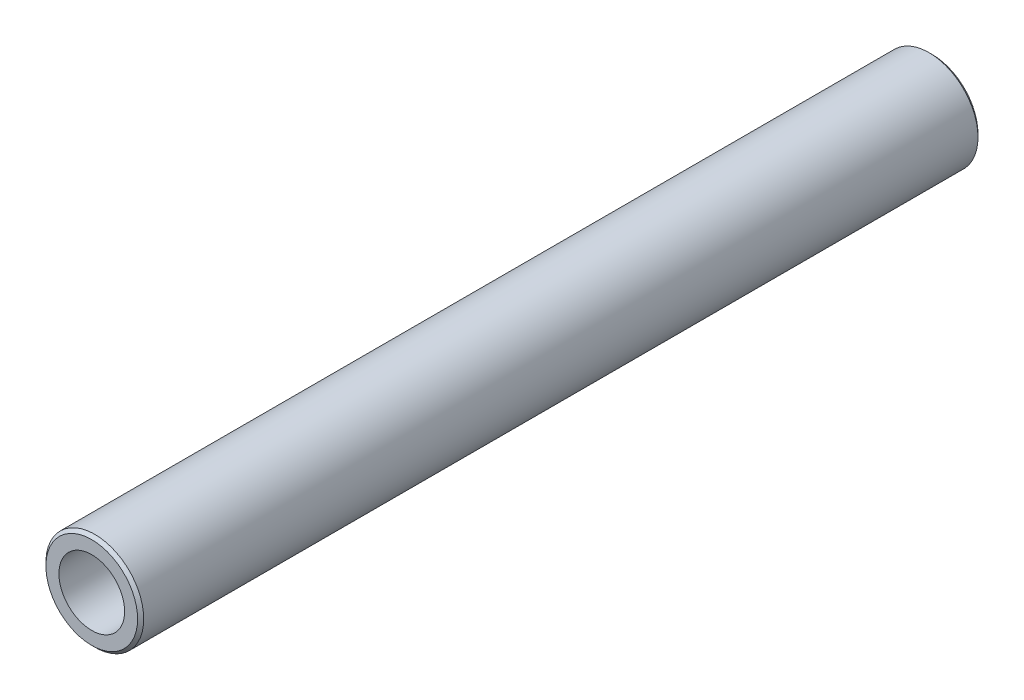
SolidWorks part; units mm, degrees
ref_plane "Front Plane" through (0, 0, 0) normal (0, 0, 1) x (1, 0, 0)
ref_plane "Top Plane" through (0, 0, 0) normal (0, 1, 0) x (1, 0, 0)
ref_plane "Right Plane" through (0, 0, 0) normal (1, 0, 0) x (0, 0, -1)
sketch "Sketch1" plane through (0, 0, 0) normal (0, 0, 1) x (1, 0, 0)
  circle A0 centre (0, 0) radius 6.4
  circle A1 centre (0, 0) radius 4.3
  dimension "D1" = 2.1
  dimension "D2" = 8.6
extrude "Boss-Extrude1" add sketch "Sketch1" along normal blind 110
chamfer "Chamfer1" distance 0.4 angle 45 2 edges at (6.4, 0, 110) (6.4, 0, 0)
